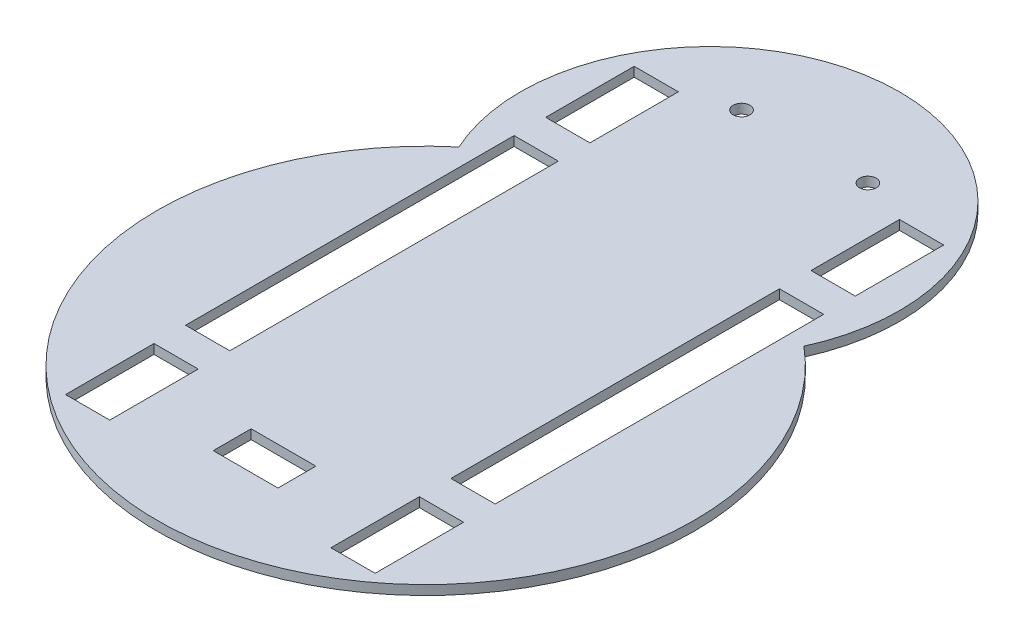
SolidWorks part; units mm, degrees
ref_plane "Alzado" through (0, 0, 0) normal (0, 0, 1) x (1, 0, 0)
ref_plane "Planta" through (0, 0, 0) normal (0, 1, 0) x (1, 0, 0)
ref_plane "Vista lateral" through (0, 0, 0) normal (1, 0, 0) x (0, 0, -1)
sketch "Croquis1" plane through (0, 0, 0) normal (0, 1, 0) x (1, 0, 0)
  line L0 (-95.7269, 150) -> (103.8723, 150) construction
  line L1 (0, -64.5682) -> (0, 164.9867) construction
  line L2 (94.4126, -85) -> (-166.6745, -85) construction
  line L3 (49, 115) -> (35, 115)
  line L4 (-49, -65) -> (-35, -65)
  line L5 (-49, -65) -> (-49, 115)
  line L6 (-49, 115) -> (-35, 115)
  line L7 (-35, -65) -> (-35, 115)
  line L8 (35, -65) -> (35, 115)
  line L9 (49, -65) -> (35, -65)
  line L10 (49, -65) -> (49, 115)
  line L11 (49, -27) -> (35, -27)
  line L12 (-49, 77) -> (-35, 77)
  line L13 (-49, 77) -> (-49, 87)
  line L14 (-49, 87) -> (-35, 87)
  line L15 (-35, 77) -> (-35, 87)
  line L16 (-49, -37) -> (-35, -37)
  line L17 (-49, -37) -> (-49, -27)
  line L18 (-49, -27) -> (-35, -27)
  line L19 (-35, -37) -> (-35, -27)
  line L20 (35, -37) -> (35, -27)
  line L21 (49, -37) -> (35, -37)
  line L22 (49, -37) -> (49, -27)
  line L23 (49, 87) -> (35, 87)
  line L24 (35, 77) -> (35, 87)
  line L25 (49, 77) -> (35, 77)
  line L26 (49, 77) -> (49, 87)
  circle A0 centre (0, 90) radius 60
  circle A1 centre (0, 0) radius 85
  point P27 (-42, -65)
  dimension "D1" = 170
  dimension "D2" = 120
  dimension "D3" = 150
  dimension "D4" = 235
  dimension "D5" = 14
  dimension "D6" = 35
  dimension "D7" = 115
  dimension "D8" = 180
  dimension "D9" = 28
  dimension "D10" = 10
  dimension "D11" = 28
  dimension "D12" = 10
extrude "Saliente-Extruir1" add sketch "Croquis1" along normal mid plane 3 contours A0 A1 L10 L9 L8 L7 L4 L5 | L8 A1 L7 A0 | L5 A1 A0 | A1 A0 L5 L6 L7 L8 L3 L10 | A0 A1 L10 | L17 L16 L19 L18 | L11 L20 L21 L22 | L23 L24 L25 L26 | L13 L12 L15 L14
sketch "Croquis2" plane through (0, -1.5, 0) normal (0, -1, 0) x (1, 0, 0)
  line L0 (0, 0) -> (0, 97.5027) construction
  line L1 (-10.25, 57) -> (10.25, 57)
  line L2 (-10.25, 57) -> (-10.25, 45)
  line L3 (-10.25, 45) -> (10.25, 45)
  line L4 (10.25, 57) -> (10.25, 45)
  line L5 (0, 0) -> (0, -142.6893) construction
  line L6 (-20, -111.4832) -> (-20, -130.0963) construction
  line L7 (20, -129.2986) -> (20, -111.4832) construction
  line L8 (-28.6668, -120) -> (31.6195, -120) construction
  line L9 (-95.8372, 0) -> (105.427, 0) construction
  circle A0 centre (-20, -120) radius 2.65
  circle A1 centre (20, -120) radius 2.65
  point P7 (0, 57)
  point P21 (0, 0)
  point P22 (0, 0)
  point P23 (0, 0)
  point P24 (0, 0)
  dimension "D4" = 5.3
  dimension "D1" = 45
  dimension "D2" = 12
  dimension "D3" = 20.5
  dimension "D5" = 120
  dimension "D6" = 20
extrude "Cortar-Extruir1" cut sketch "Croquis2" against normal blind 10
